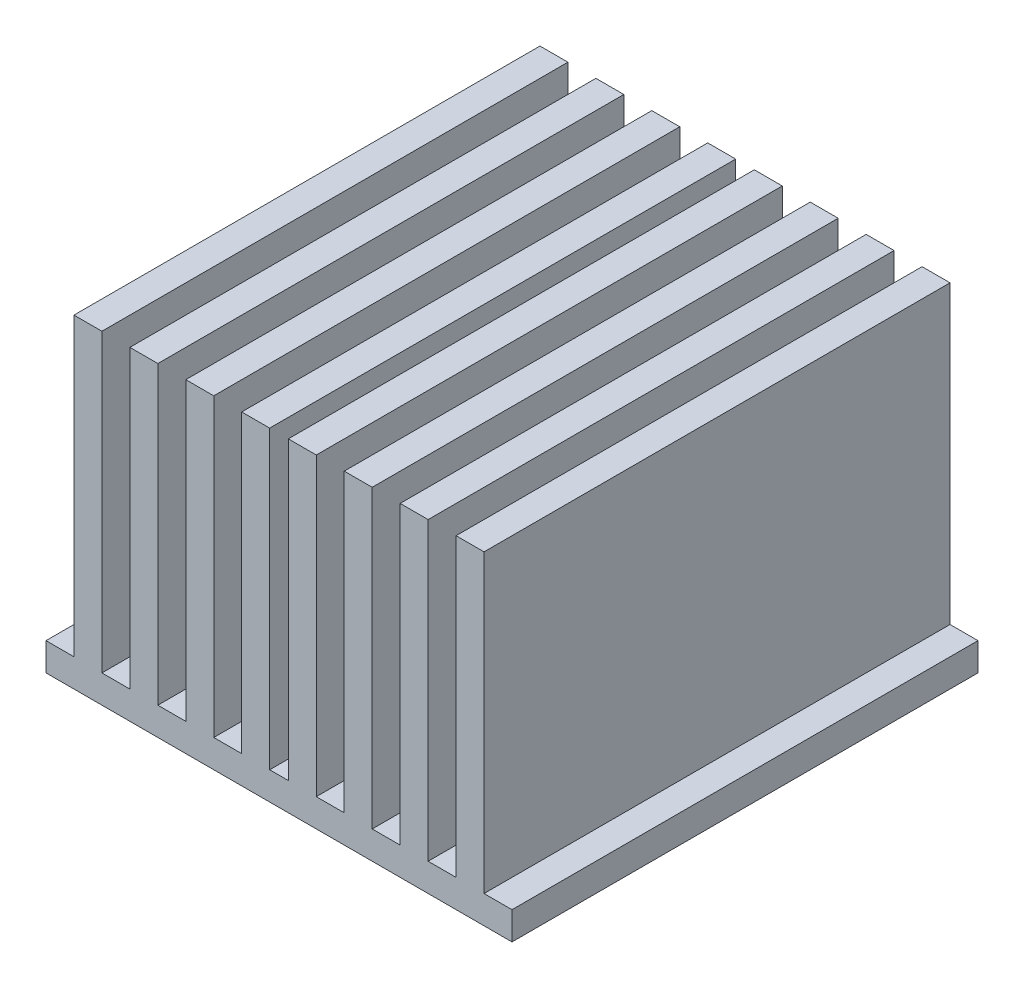
SolidWorks part; units mm, degrees
material "Copper"
ref_plane "Front Plane" through (0, 0, 0) normal (0, 0, 1) x (1, 0, 0)
ref_plane "Top Plane" through (0, 0, 0) normal (0, 1, 0) x (1, 0, 0)
ref_plane "Right Plane" through (0, 0, 0) normal (1, 0, 0) x (0, 0, -1)
sketch "Sketch2" plane through (0, 0, 0) normal (0, 1, 0) x (1, 0, 0)
  line L1 (0, 0) -> (50, 0)
  line L2 (0, 0) -> (0, 50)
  line L3 (0, 50) -> (50, 50)
  line L4 (50, 0) -> (50, 50)
  dimension "D1" = 50
  dimension "D2" = 50
extrude "Boss-Extrude1" add sketch "Sketch2" along normal blind 3
sketch "Sketch3" plane through (0, 3, 0) normal (0, 1, 0) x (1, 0, 0)
  line L0 (50, 50) -> (0, 50) construction
  line L1 (3, 50) -> (6, 50)
  line L2 (3, 50) -> (3, 0)
  line L3 (3, 0) -> (6, 0)
  line L4 (6, 50) -> (6, 0)
  line L5 (0, 0) -> (50, 0) construction
  line L6 (0, 50) -> (0, 0) construction
  line L7 (25, 50) -> (25, 0) construction
  line L8 (12, 50) -> (12, 0)
  line L9 (9, 50) -> (9, 0)
  line L10 (9, 50) -> (12, 50)
  line L11 (9, 0) -> (12, 0)
  line L12 (18, 50) -> (18, 0)
  line L13 (15, 50) -> (15, 0)
  line L14 (15, 50) -> (18, 50)
  line L15 (15, 0) -> (18, 0)
  line L16 (24, 50) -> (24, 0)
  line L17 (21, 50) -> (21, 0)
  line L18 (21, 50) -> (24, 50)
  line L19 (21, 0) -> (24, 0)
  dimension "D2" = 3
  dimension "D1" = 3
  dimension "D4" = 3
  dimension "D3" = 4
extrude "Boss-Extrude2" add sketch "Sketch3" along normal blind 31.75
ref_plane "Plane1" through (25, 0, 0) normal (-1, 0, 0) x (0, 0, 1)
mirror "Mirror1" about plane through (25, 0, 0) normal (-1, 0, 0) of "Boss-Extrude2"
equation "\"t_fin\" = 3mm"
equation "\"g_fin\"= 3mm"
equation "\"L_tot\"= 50mm"
equation "\"L_fin\"= \"L_tot\" - 2 * \"g_fin\""
equation "\"N_fins\"= ( \"g_fin\" + \"L_fin\" ) / ( ( \"g_fin\" + \"t_fin\" ) * 2 )"
equation "\"D3@Sketch3\"=\"N_fins\""
equation "\"D2@Sketch3\"=\"g_fin\""
equation "\"D1@Sketch3\"=\"t_fin\""
equation "\"D4@Sketch3\"=\"g_fin\""
